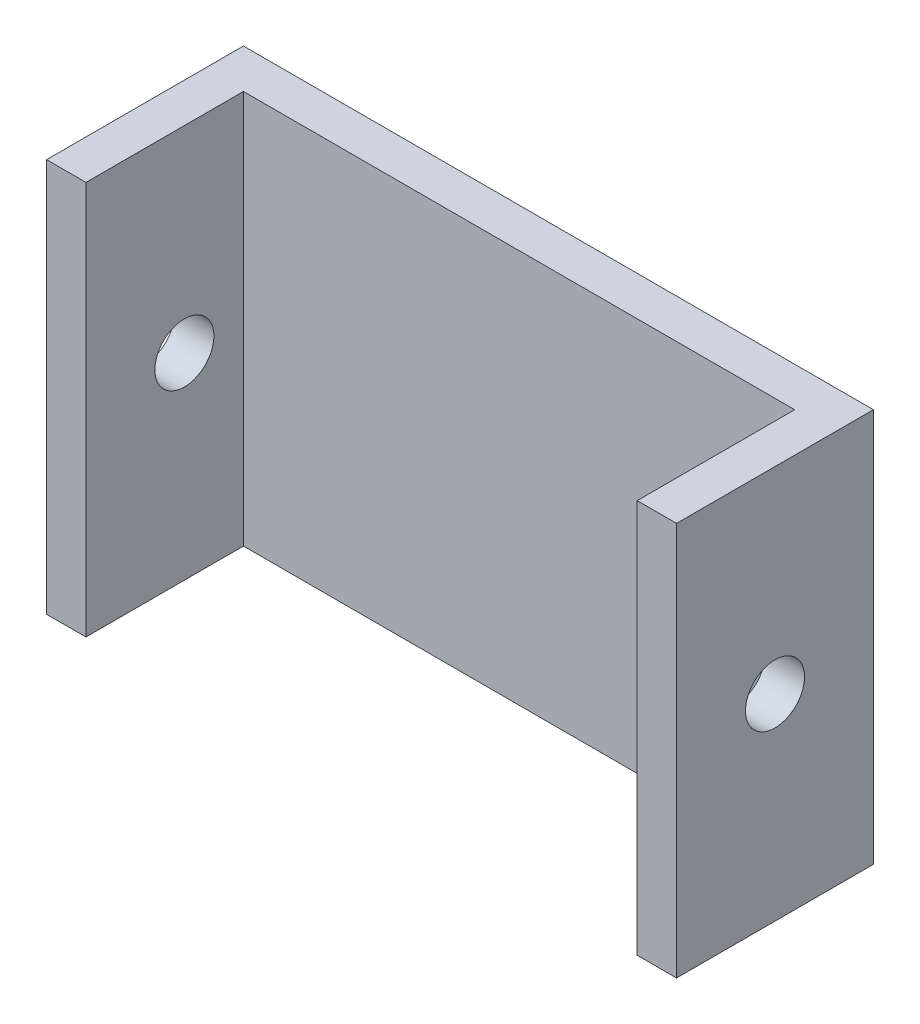
SolidWorks part; units mm, degrees
ref_plane "Plan de face" through (0, 0, 0) normal (0, 0, 1) x (1, 0, 0)
ref_plane "Plan de dessus" through (0, 0, 0) normal (0, 1, 0) x (1, 0, 0)
ref_plane "Plan de droite" through (0, 0, 0) normal (1, 0, 0) x (0, 0, -1)
sketch "Esquisse1" plane through (0, 0, 0) normal (0, 0, 1) x (1, 0, 0)
  line L1 (-14, 10) -> (14, 10)
  line L2 (-14, 10) -> (-14, -10)
  line L3 (-14, -10) -> (14, -10)
  line L4 (14, 10) -> (14, -10)
  line L5 (-14, 10) -> (14, -10) construction
  line L6 (-14, -10) -> (14, 10) construction
  point P0 (0, 0)
  dimension "D1" = 28
  dimension "D2" = 20
extrude "Boss.-Extru.1" add sketch "Esquisse1" along normal blind 2
sketch "Esquisse2" plane through (0, 0, 0) normal (0, 0, 1) x (1, 0, 0)
  line L0 (-14, -10) -> (-16, -10)
  line L1 (-16, -10) -> (-16, 10)
  line L2 (-16, 10) -> (-14, 10)
  line L3 (-14, 10) -> (-14, -10)
  line L8 (0, -13.5768) -> (0, 16.1891) construction
  line L9 (16, 10) -> (14, 10)
  line L10 (16, -10) -> (16, 10)
  line L11 (14, -10) -> (16, -10)
  line L12 (14, 10) -> (14, -10)
  dimension "D1" = 2
extrude "Boss.-Extru.2" add sketch "Esquisse2" along normal blind 10
sketch "Esquisse3" plane through (0, 0, 0) normal (1, 0, 0) x (0, 0, -1)
  circle A0 centre (-5, 0) radius 1.5
  point P2 (0, 0)
  dimension "D2" = 3
  dimension "D1" = 5
extrude "Enlèv. mat.-Extru.1" cut sketch "Esquisse3" against normal through all both and the other way through all
